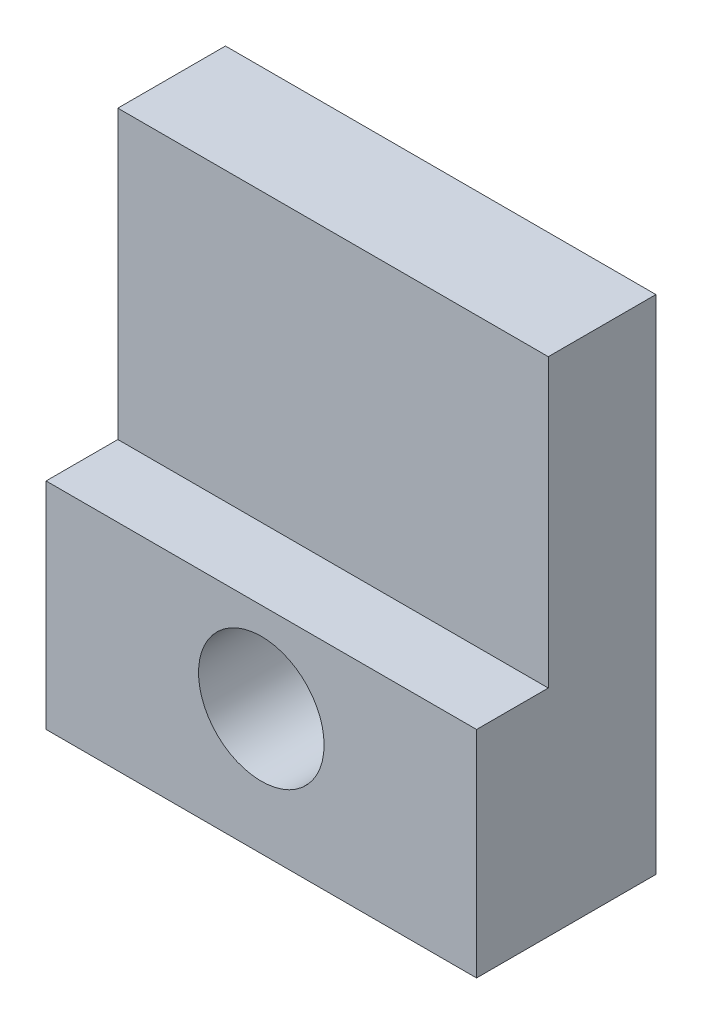
SolidWorks part; units mm, degrees
ref_plane "Спереди" through (0, 0, 0) normal (0, 0, 1) x (1, 0, 0)
ref_plane "Сверху" through (0, 0, 0) normal (0, 1, 0) x (1, 0, 0)
ref_plane "Справа" through (0, 0, 0) normal (1, 0, 0) x (0, 0, -1)
sketch "Эскиз1" plane through (0, 0, 0) normal (0, 0, 1) x (1, 0, 0)
  line L0 (0, 51.2799) -> (0, -43.7387) construction
  line L1 (-34.5008, 0) -> (33.3696, 0) construction
  line L3 (-6, 7) -> (6, 7)
  line L4 (-6, 7) -> (-6, -7)
  line L5 (-6, -7) -> (6, -7)
  line L6 (6, 7) -> (6, -7)
  circle A0 centre (0, -3.5) radius 1.75
  dimension "D3" = 3.5
  dimension "D1" = 12
  dimension "D2" = 14
  dimension "D4" = 3.5
extrude "Вытянуть1" add sketch "Эскиз1" along normal blind 5
sketch "Эскиз2" plane through (0, 0, 5) normal (0, 0, 1) x (1, 0, 0)
  line L0 (-6, -7) -> (6, -7) construction
  line L1 (-8.2723, -1) -> (7.8105, -1)
  line L2 (-8.2723, -1) -> (-8.2723, 9)
  line L3 (-8.2723, 9) -> (7.8105, 9)
  line L4 (7.8105, -1) -> (7.8105, 9)
  dimension "D1" = 6
  dimension "D2" = 10
extrude "Вырез-Вытянуть1" cut sketch "Эскиз2" against normal blind 2
